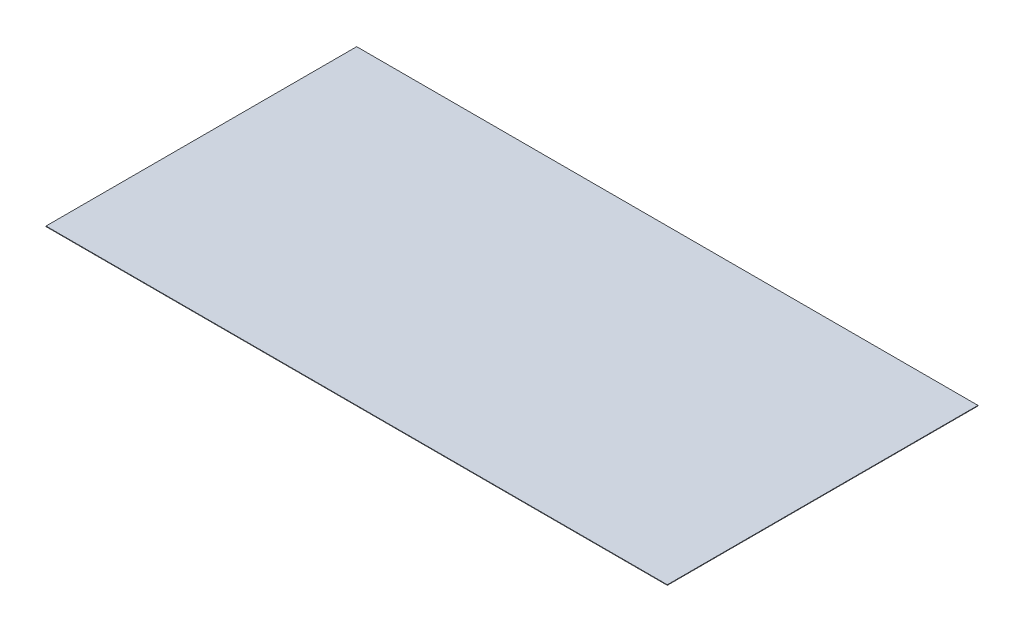
SolidWorks part; units mm, degrees
ref_plane "Front Plane" through (0, 0, 0) normal (0, 0, 1) x (1, 0, 0)
ref_plane "Top Plane" through (0, 0, 0) normal (0, 1, 0) x (1, 0, 0)
ref_plane "Right Plane" through (0, 0, 0) normal (1, 0, 0) x (0, 0, -1)
sketch "Sketch1" plane through (0, 0, 0) normal (0, 1, 0) x (1, 0, 0)
  line L1 (-3044, 1522) -> (3044, 1522)
  line L2 (-3044, 1522) -> (-3044, -1522)
  line L3 (-3044, -1522) -> (3044, -1522)
  line L4 (3044, 1522) -> (3044, -1522)
  line L5 (-3044, 1522) -> (3044, -1522) construction
  line L6 (-3044, -1522) -> (3044, 1522) construction
  point P0 (0, 0)
  dimension "D1" = 3044
  dimension "D2" = 6088
extrude "Boss-Extrude1" add sketch "Sketch1" along normal blind 5
